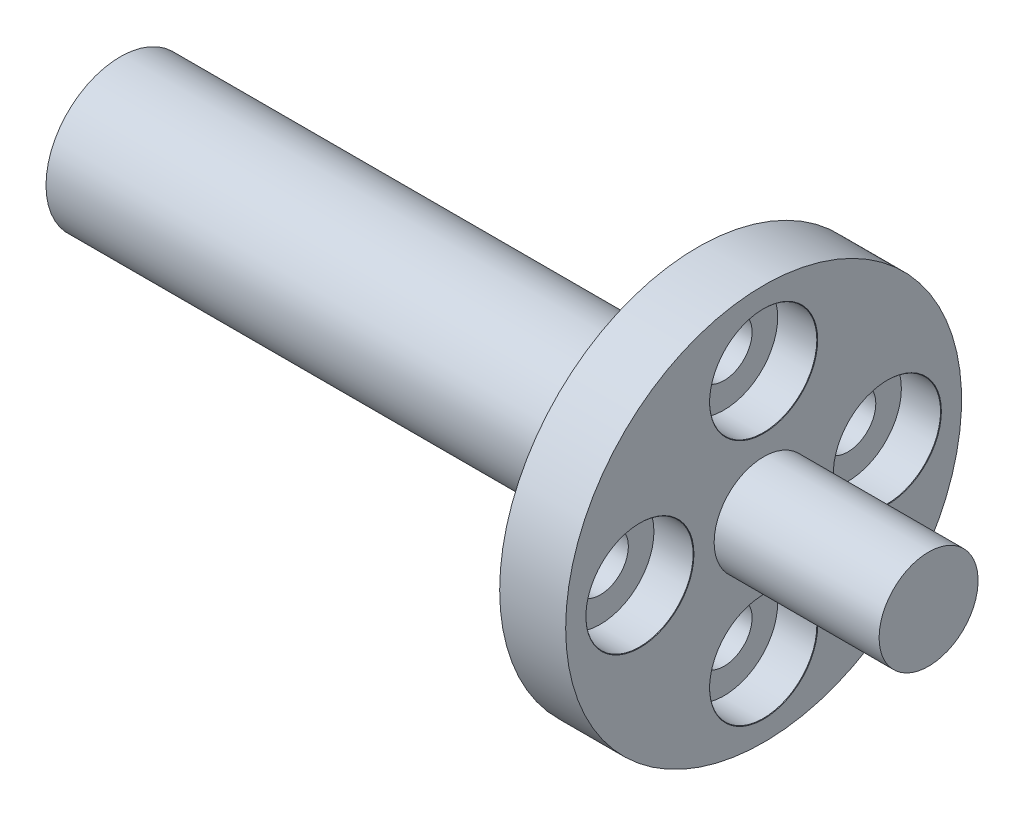
SolidWorks part; units mm, degrees
ref_plane "Front Plane" through (0, 0, 0) normal (0, 0, 1) x (1, 0, 0)
ref_plane "Top Plane" through (0, 0, 0) normal (0, 1, 0) x (1, 0, 0)
ref_plane "Right Plane" through (0, 0, 0) normal (1, 0, 0) x (0, 0, -1)
sketch "Sketch1" plane through (0, 0, 0) normal (0, 0, 1) x (1, 0, 0)
  line L0 (49, 0) -> (49, 3)
  line L1 (49, 3) -> (39, 3)
  line L2 (39, 3) -> (39, 12)
  line L3 (39, 12) -> (35, 12)
  line L4 (35, 12) -> (35, 4.5)
  line L5 (35, 4.5) -> (0, 4.5)
  line L6 (0, 4.5) -> (0, 0)
  line L7 (0, 0) -> (49, 0)
  point P2 (0, 0)
  dimension "D1" = 12
  dimension "D2" = 4.5
  dimension "D3" = 10
  dimension "D4" = 35
  dimension "D5" = 4
  dimension "D6" = 3
revolve "Revolve1" add sketch "Sketch1" angle 360 about L7
sketch "Sketch2" plane through (39, 0, 0) normal (1, 0, 0) x (0, 0, -1)
  circle A0 centre (0, 0) radius 7.5 construction
  point P4 (0, 7.5)
  point P12 (7.5, 0)
  point P13 (0, -7.5)
  point P14 (-7.5, 0)
  dimension "D1" = 15
  dimension "D2" = 4
hole_wizard "CBORE for M3 Hex Socket Thin Head Cap Screw1" positions "Sketch2" profile "Sketch3" counterbore size "M3" standard "DIN" end condition through all
sketch "Sketch3" plane through (39, 0, 7.5) normal (0, 1, 0) x (0, 0, -1)
  line L0 (0, 0) -> (0, 39)
  line L1 (0, 39) -> (1.7, 39)
  line L3 (1.7, 39) -> (1.7, 2.4)
  line L4 (3.25, 2.4) -> (1.7, 2.4)
  line L5 (3.25, 2.4) -> (3.25, 0.025)
  line L6 (3.25, 0.025) -> (3.275, 0)
  line L7 (3.275, 0) -> (0, 0)
  line L8 (-3.25, 0.025) -> (-3.275, 0) construction
  line L11 (0, -6.35) -> (0, 107.95) construction
  dimension "Thru Hole Dia." = 3.4
  dimension "Thru Hole Depth" = 39
  dimension "C'Bore Dia." = 6.5
  dimension "C'Bore Depth" = 2.4
  dimension "Near C'Sink Dia." = 6.55
  dimension "Near C'Sink Angle" = 90
